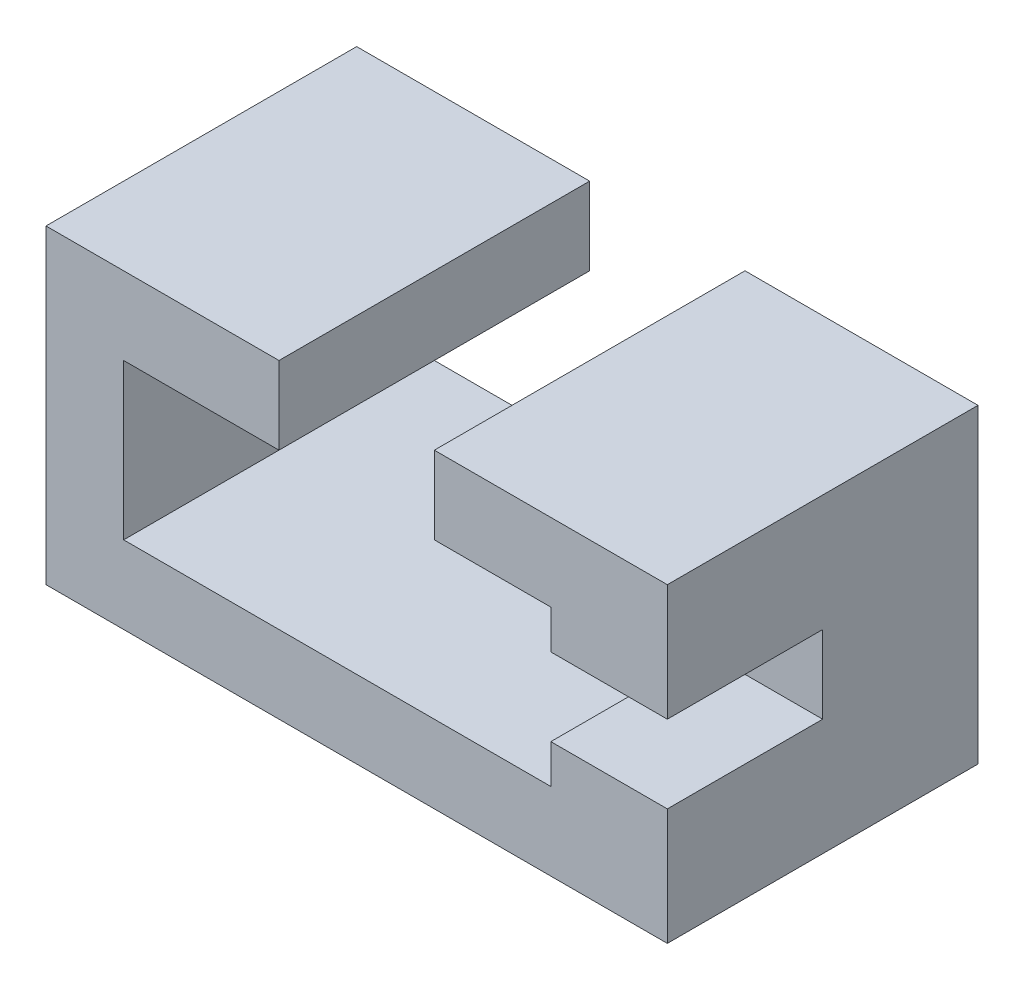
SolidWorks part; units mm, degrees
ref_plane "Front Plane" through (0, 0, 0) normal (0, 0, 1) x (1, 0, 0)
ref_plane "Top Plane" through (0, 0, 0) normal (0, 1, 0) x (1, 0, 0)
ref_plane "Right Plane" through (0, 0, 0) normal (1, 0, 0) x (0, 0, -1)
sketch "Sketch1" plane through (0, 0, 0) normal (0, 0, 1) x (1, 0, 0)
  line L1 (-40, -20) -> (40, -20)
  line L2 (-40, -20) -> (-40, 20)
  line L3 (-40, 20) -> (40, 20)
  line L4 (40, -20) -> (40, 20)
  line L5 (-40, -20) -> (40, 20) construction
  line L6 (-40, 20) -> (40, -20) construction
  point P0 (0, 0)
  dimension "D1" = 80
  dimension "D2" = 40
extrude "Boss-Extrude1" add sketch "Sketch1" along normal blind 40
sketch "Sketch2" plane through (0, 0, 40) normal (0, 0, 1) x (1, 0, 0)
  line L0 (-40, 20) -> (-40, -20) construction
  line L1 (-30, 10) -> (25, 10)
  line L2 (-30, 10) -> (-30, -10)
  line L3 (-30, -10) -> (25, -10)
  line L4 (25, 10) -> (25, -10)
  line L5 (-40, -20) -> (40, -20) construction
  line L6 (40, 20) -> (-40, 20) construction
  line L7 (40, -20) -> (40, 20) construction
  dimension "D1" = 10
  dimension "D2" = 10
  dimension "D3" = 10
  dimension "D4" = 55
  dimension "D5" = 15
extrude "Cut-Extrude1" cut sketch "Sketch2" against normal blind 40
sketch "Sketch4" plane through (0, 0, 40) normal (0, 0, 1) x (1, 0, 0)
  line L1 (40, -20) -> (40, 20) construction
  line L2 (25, -10) -> (25, 10) construction
  line L3 (40, -5) -> (25, -5)
  line L4 (40, -5) -> (40, 5)
  line L5 (40, 5) -> (25, 5)
  line L6 (25, -5) -> (25, 5)
  line L7 (-40, -20) -> (40, -20) construction
  dimension "D1" = 10
  dimension "D2" = 15
extrude "Cut-Extrude2" cut sketch "Sketch4" against normal blind 20
sketch "Sketch5" plane through (0, 0, 40) normal (0, 0, 1) x (1, 0, 0)
  line L9 (40, 20) -> (-40, 20) construction
  line L11 (25, 10) -> (-30, 10) construction
  line L12 (-10, 20) -> (10, 20)
  line L13 (-10, 20) -> (-10, 10)
  line L14 (-10, 10) -> (10, 10)
  line L15 (10, 20) -> (10, 10)
extrude "Cut-Extrude3" cut sketch "Sketch5" against normal through all
